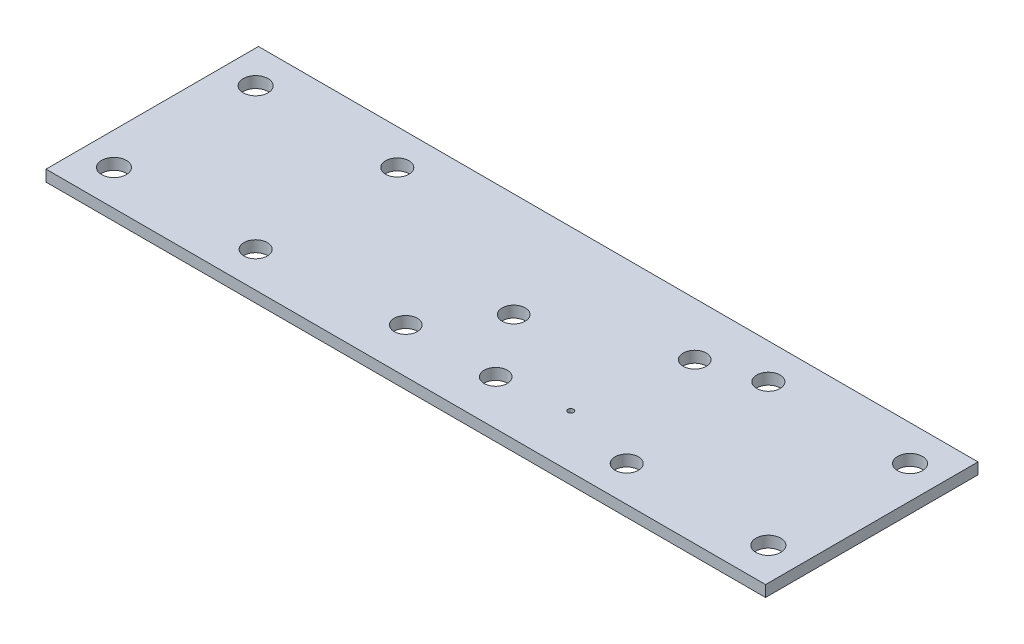
SolidWorks part; units mm, degrees
ref_plane "Front Plane" through (0, 0, 0) normal (0, 0, 1) x (1, 0, 0)
ref_plane "Top Plane" through (0, 0, 0) normal (0, 1, 0) x (1, 0, 0)
ref_plane "Right Plane" through (0, 0, 0) normal (1, 0, 0) x (0, 0, -1)
sketch "Sketch1" plane through (0, 0, 0) normal (0, 1, 0) x (1, 0, 0)
  line L0 (0, 0) -> (76.4014, 0) construction
  line L1 (-101.6, 30) -> (101.6, 30)
  line L2 (-101.6, 30) -> (-101.6, -30)
  line L3 (-101.6, -30) -> (101.6, -30)
  line L4 (101.6, 30) -> (101.6, -30)
  line L5 (-101.6, 30) -> (101.6, -30) construction
  line L6 (-101.6, -30) -> (101.6, 30) construction
  line L7 (0, 0) -> (0, 23.5578) construction
  circle A0 centre (-52.4, 20) radius 3.3
  circle A1 centre (-92.4, -20) radius 3.5
  circle A2 centre (-52.4, -20) radius 3.3
  circle A3 centre (92.4, 20) radius 3.5
  circle A4 centre (-92.4, 20) radius 3.5
  circle A5 centre (52.4, -20) radius 3.3
  circle A6 centre (92.4, -20) radius 3.5
  circle A7 centre (52.4, 20) radius 3.3
  point P0 (0, 0)
  dimension "D1" = 6.6
  dimension "D4" = 7
  dimension "D2" = 40
  dimension "D5" = 40
  dimension "D6" = 60
  dimension "D7" = 9.2
  dimension "D8" = 203.2
extrude "Boss-Extrude1" add sketch "Sketch1" along normal blind 3.175
sketch "Sketch2" plane through (0, 3.175, 0) normal (0, 1, 0) x (1, 0, 0)
  line L0 (12.7, -17.3) -> (-12.7, -17.3) construction
  line L1 (-101.6, -30) -> (101.6, -30) construction
  circle A0 centre (-12.7, -17.3) radius 3.2639
  circle A1 centre (12.7, -17.3) radius 3.2639
  circle A2 centre (0, 0.48) radius 3.2639
  point P6 (0, -17.3)
  dimension "D1" = 12.7
  dimension "D2" = 6.5278
  dimension "D3" = 25.4
  dimension "D4" = 17.78
extrude "1/4-20 for Nut Bracket" cut sketch "Sketch2" against normal through all
sketch "Sketch3" plane through (0, 3.175, 0) normal (0, 1, 0) x (1, 0, 0)
  line L0 (-101.6, -30) -> (101.6, -30) construction
  line L1 (101.6, -30) -> (101.6, 30) construction
  circle A0 centre (31.6, -15) radius 0.7937
  circle A1 centre (36.6, 15) radius 3.2639
  point P6 (0, 0)
  point P7 (0, 0)
  point P8 (0, 0)
  point P9 (0, 0)
  dimension "D1" = 1.5875
  dimension "D3" = 6.5278
  dimension "D2" = 15
  dimension "D4" = 70
  dimension "D5" = 30
  dimension "D6" = 65
extrude "Wire Holder" cut sketch "Sketch3" against normal through all
